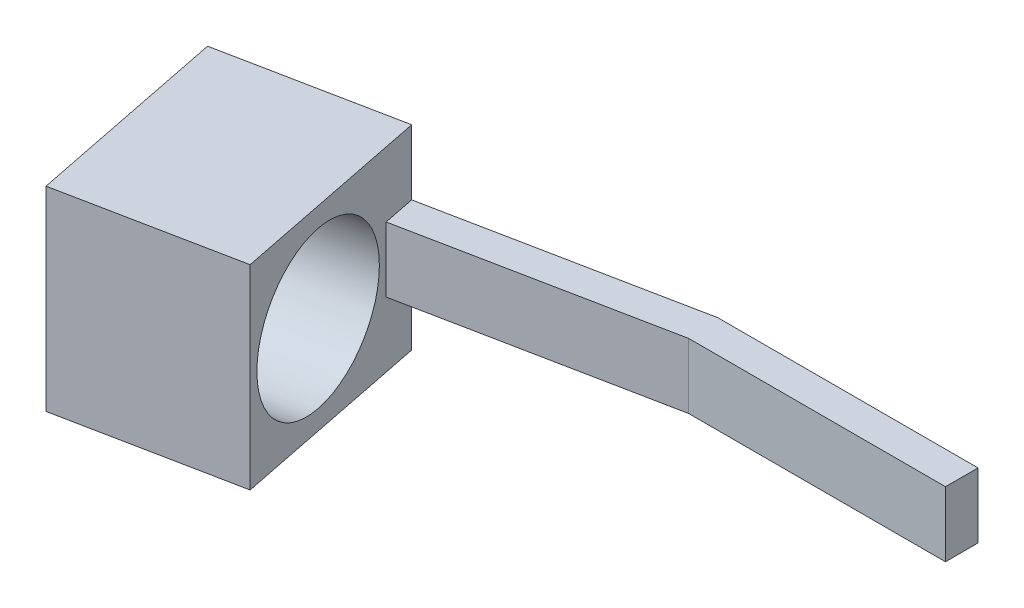
SolidWorks part; units mm, degrees
ref_plane "Front Plane" through (0, 0, 0) normal (0, 0, 1) x (1, 0, 0)
ref_plane "Top Plane" through (0, 0, 0) normal (0, 1, 0) x (1, 0, 0)
ref_plane "Right Plane" through (0, 0, 0) normal (1, 0, 0) x (0, 0, -1)
sketch "Sketch1" plane through (0, 0, 0) normal (0, 1, 0) x (1, 0, 0)
  line L0 (0, 0) -> (12, 0)
  line L1 (12, 0) -> (12, 1.5)
  line L2 (12, 1.5) -> (0, 1.5)
  line L3 (0, 1.5) -> (0, 0)
extrude "Boss-Extrude1" add sketch "Sketch1" along normal blind 3
sketch "Sketch2" plane through (0, 3, 0) normal (0, 1, 0) x (1, 0, 0)
  line L0 (0, 1.5) -> (-11.767, -0.8534)
  line L2 (-11.767, -0.8534) -> (-11.4728, -2.3243)
  line L3 (-11.4728, -2.3243) -> (0.2942, 0.0291)
  line L4 (0, 1.5) -> (0.2942, 0.0291)
extrude "Boss-Extrude2" add sketch "Sketch2" against normal blind 3
sketch "Sketch4" plane through (0, 3, 0) normal (0, 1, 0) x (1, 0, 0)
  line L0 (-11.767, -0.8534) -> (-9.9039, -10.1689)
  line L1 (-9.9039, -10.1689) -> (-17.7485, -11.7378)
  line L2 (-11.767, -0.8534) -> (-19.6116, -2.4223)
  line L3 (-19.6116, -2.4223) -> (-17.7485, -11.7378)
extrude "Boss-Extrude3" add sketch "Sketch4" along normal blind 3 and the other way blind 6
hole_wizard "#97 (0.0059) Diameter Hole1" positions "Sketch6" profile "Sketch7" hole size "#97" standard "ANSI Inch"
sketch "Sketch6" plane through (-19.3232, 0, 3.8646) normal (-0.9806, 0, 0.1961) x (0.1961, 0, 0.9806)
  line L0 (8.0291, -3) -> (8.0291, 6) construction
  point P0 (4.0291, 1.5)
  dimension "D1" = 4
sketch "Sketch7" plane through (-18.533, 1.5, 7.8155) normal (0, 1, 0) x (0.1961, 0, 0.9806)
  line L0 (0, 0) -> (0, 10)
  line L1 (0, 10) -> (3.6, 10)
  line L2 (3.6, 10) -> (3.6, 0)
  line L5 (3.6, 0) -> (0, 0)
  line L10 (0, 10) -> (-3.6, 10) construction
  line L11 (0, -6.35) -> (0, 107.95) construction
  dimension "Hole Dia." = 7.2
  dimension "Hole Depth" = 10
  dimension "Drill Angle" = 180
